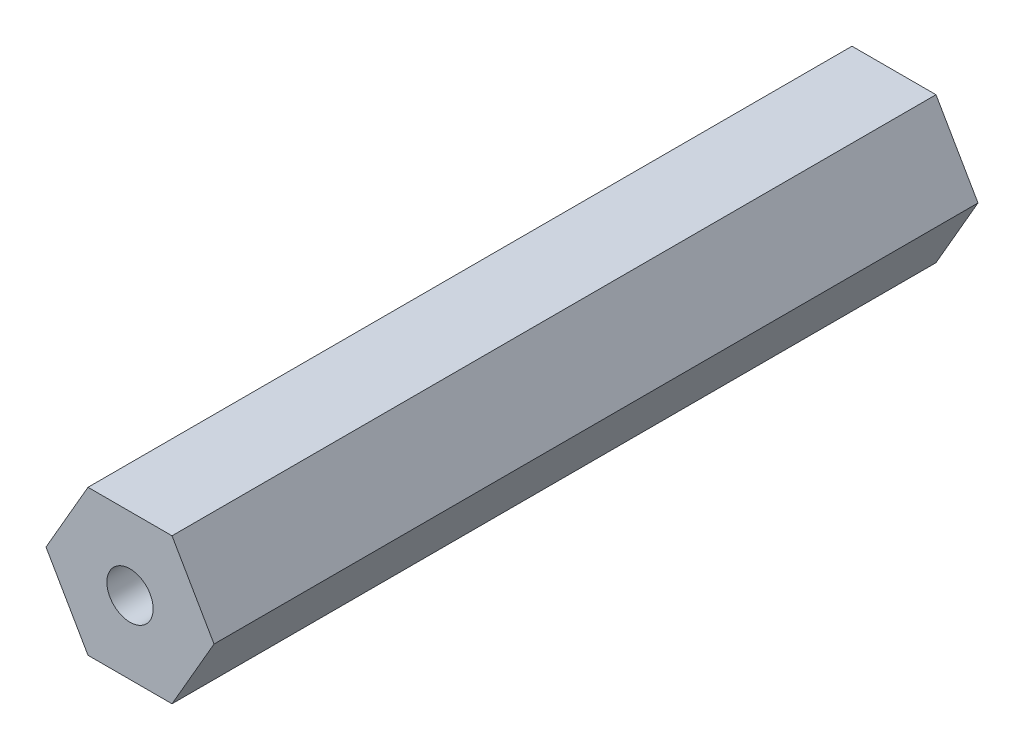
SolidWorks part; units mm, degrees
material "6061-T6 (SS)"
ref_plane "Front Plane" through (0, 0, 0) normal (0, 0, 1) x (1, 0, 0)
ref_plane "Top Plane" through (0, 0, 0) normal (0, 1, 0) x (1, 0, 0)
ref_plane "Right Plane" through (0, 0, 0) normal (1, 0, 0) x (0, 0, -1)
sketch "Sketch1" plane through (0, 0, 0) normal (0, 0, 1) x (1, 0, 0)
  line L1 (-7.3323, 0) -> (-3.6662, -6.35)
  line L2 (-3.6662, -6.35) -> (3.6662, -6.35)
  line L3 (3.6662, -6.35) -> (7.3323, 0)
  line L4 (7.3323, 0) -> (3.6662, 6.35)
  line L5 (3.6662, 6.35) -> (-3.6662, 6.35)
  line L6 (-3.6662, 6.35) -> (-7.3323, 0)
  circle A0 centre (0, 0) radius 4.7625 construction
  circle A1 centre (0, 0) radius 6.35 construction
  dimension "D1" = 9.525
  dimension "D2" = 12.7
extrude "Boss-Extrude1" add sketch "Sketch1" along normal mid plane 66.675
hole_wizard "#10-32 Tapped Hole1" positions "3DSketch1" profile "Sketch2" tap size "#10-32" standard "ANSI Inch"
sketch3d "3DSketch1"
  point P0 (0, 0, 33.3375)
  point P4 (0, 0, -33.3375)
  point P5 (0, 0, 0)
  point P6 (0, 0, 0)
  point P7 (0, 0, 0)
  point P8 (0, 0, 0)
  point P9 (0, 0, 0)
  point P10 (0, 0, 0)
sketch "Sketch2" plane through (0, 0, 33.3375) normal (1, 0, 0) x (0, -1, 0)
  line L0 (0, 0) -> (0, 13.1513)
  line L1 (0, 13.1513) -> (2.0193, 11.938)
  line L2 (2.0193, 11.938) -> (2.0193, 0)
  line L5 (2.0193, 0) -> (0, 0)
  line L10 (0, 13.1513) -> (-2.0193, 11.938) construction
  line L11 (0, -6.35) -> (0, 107.95) construction
  dimension "Tap Drill Dia." = 4.0386
  dimension "Tap Drill Depth" = 11.938
  dimension "Drill Angle" = 118
cosmetic thread "Hole Thread1" parameters "D1"=9.652, "D2"=4.826
cosmetic thread "Hole Thread2" parameters "D1"=9.652, "D2"=4.826
